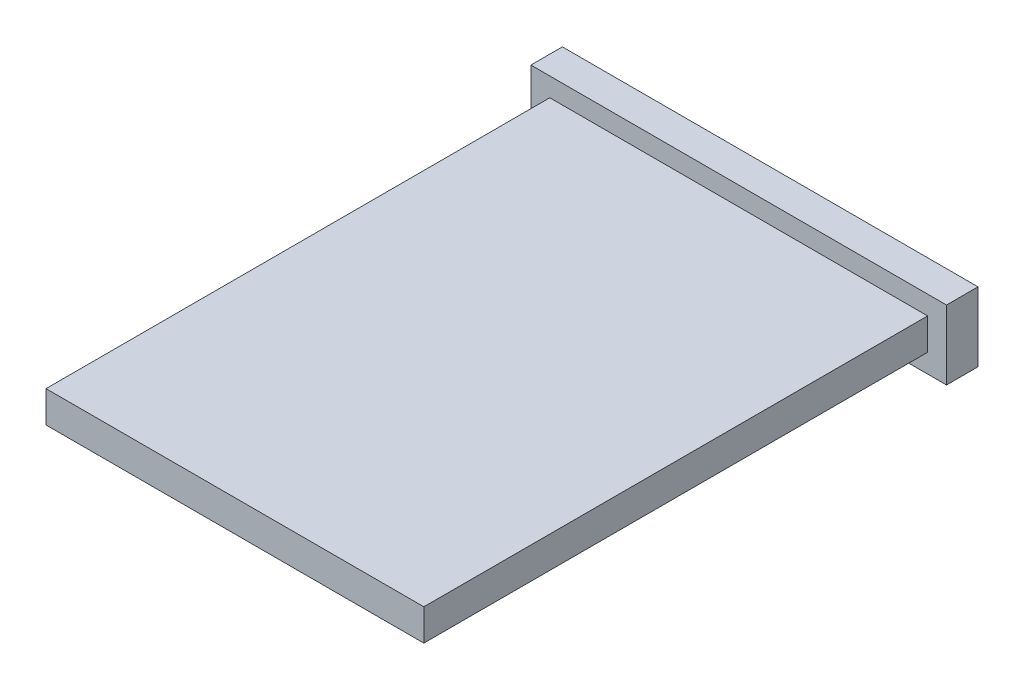
SolidWorks part; units mm, degrees
ref_plane "Front Plane" through (0, 0, 0) normal (0, 0, 1) x (1, 0, 0)
ref_plane "Top Plane" through (0, 0, 0) normal (0, 1, 0) x (1, 0, 0)
ref_plane "Right Plane" through (0, 0, 0) normal (1, 0, 0) x (0, 0, -1)
sketch "Sketch1" plane through (0, 0, 0) normal (0, 1, 0) x (1, 0, 0)
  line L1 (0, 0) -> (60, 0)
  line L2 (0, 0) -> (0, 80)
  line L3 (0, 80) -> (60, 80)
  line L4 (60, 0) -> (60, 80)
  dimension "D1" = 80
  dimension "D2" = 60
extrude "Boss-Extrude1" add sketch "Sketch1" along normal blind 5
sketch "Sketch3" plane through (0, 0, -80) normal (0, 0, -1) x (-1, 0, 0)
  line L14 (3, -3) -> (3, 8)
  line L15 (-63, -3) -> (3, -3)
  line L16 (-63, 8) -> (-63, -3)
  line L17 (3, 8) -> (-63, 8)
  line L18 (3, -3) -> (3, 8)
  line L19 (-63, -3) -> (3, -3)
  line L20 (-63, 8) -> (-63, -3)
  line L21 (3, 8) -> (-63, 8)
  dimension "D1" = 3
extrude "Boss-Extrude2" add sketch "Sketch3" along normal blind 5
